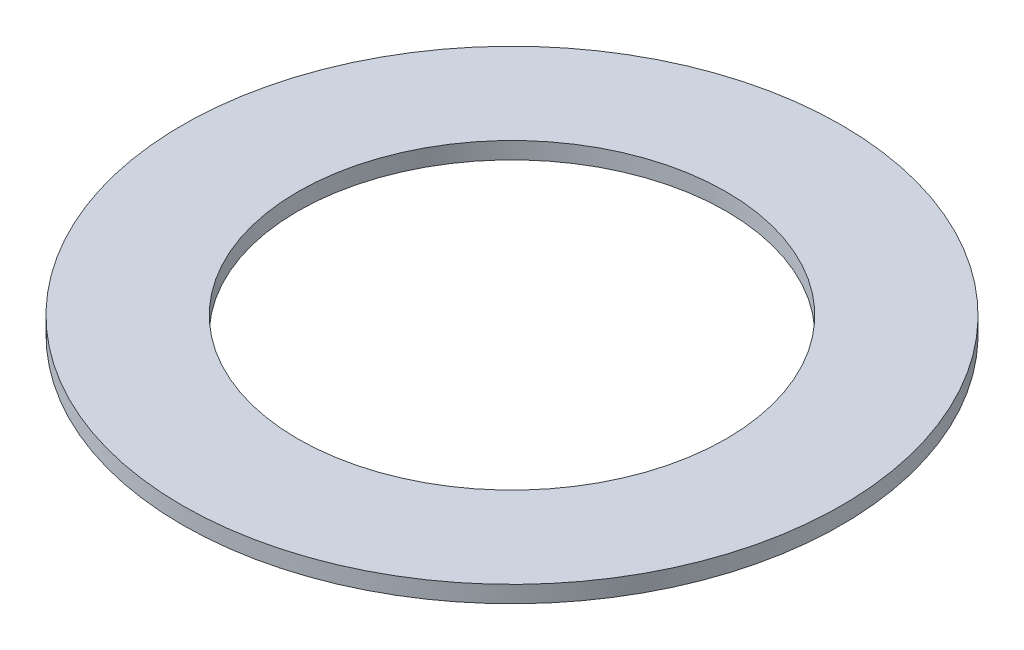
SolidWorks part; units mm, degrees
material "1060 Alloy"
ref_plane "Front Plane" through (0, 0, 0) normal (0, 0, 1) x (1, 0, 0)
ref_plane "Top Plane" through (0, 0, 0) normal (0, 1, 0) x (1, 0, 0)
ref_plane "Right Plane" through (0, 0, 0) normal (1, 0, 0) x (0, 0, -1)
sketch "Sketch1" plane through (0, 0, 0) normal (0, 1, 0) x (1, 0, 0)
  circle A0 centre (0, 0) radius 78.5
  circle A1 centre (0, 0) radius 51
  dimension "D1" = 157
  dimension "D2" = 102
extrude "Boss-Extrude1" add sketch "Sketch1" along normal blind 4
